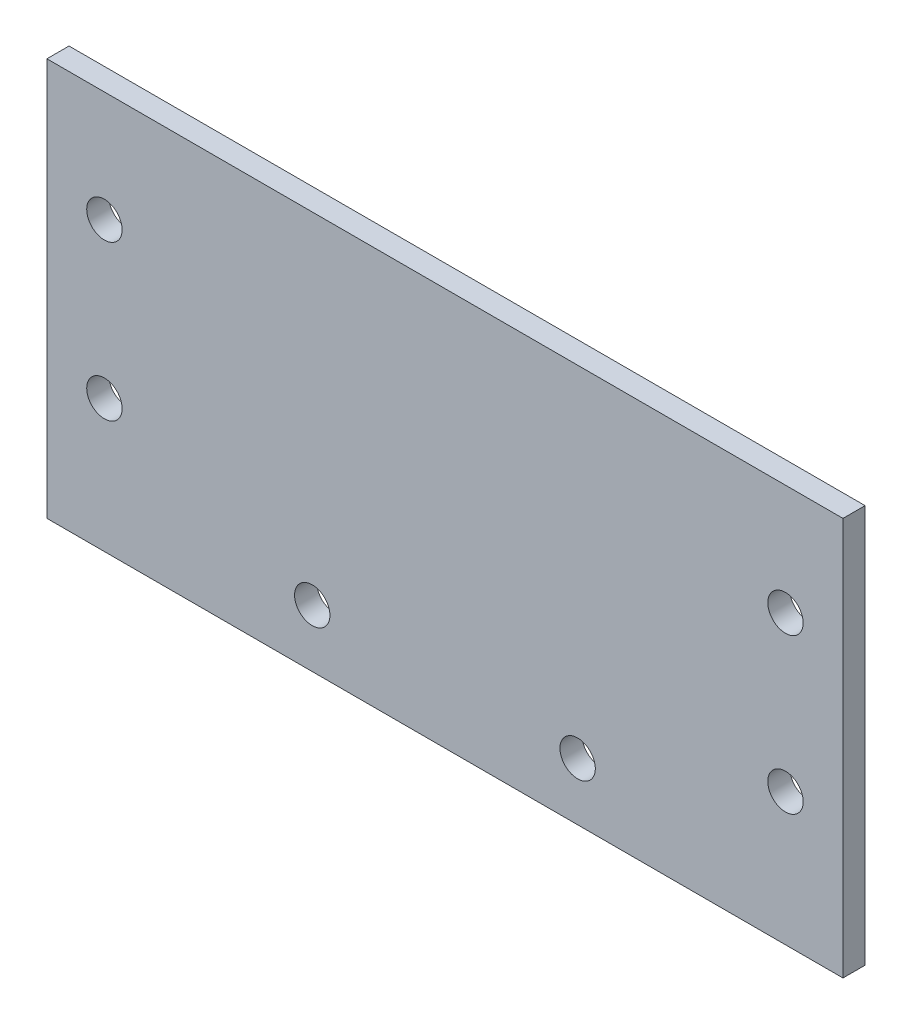
SolidWorks part; units mm, degrees
ref_plane "Front Plane" through (0, 0, 0) normal (0, 0, 1) x (1, 0, 0)
ref_plane "Top Plane" through (0, 0, 0) normal (0, 1, 0) x (1, 0, 0)
ref_plane "Right Plane" through (0, 0, 0) normal (1, 0, 0) x (0, 0, -1)
sketch "Sketch1" plane through (0, 0, 0) normal (0, 0, 1) x (1, 0, 0)
  line L1 (0, 0) -> (180, 0)
  line L2 (0, 0) -> (0, 90)
  line L3 (0, 90) -> (180, 90)
  line L4 (180, 0) -> (180, 90)
  dimension "D1" = 90
  dimension "D2" = 180
extrude "Boss-Extrude1" add sketch "Sketch1" along normal blind 5
hole_wizard "Ø1.0mm Dowel Hole1" positions "Sketch3" profile "Sketch4" hole size "Ø1.0" standard "ISO" end condition through all
sketch "Sketch3" plane through (0, 0, 0) normal (0, 0, -1) x (-1, 0, 0)
  line L0 (-180, 0) -> (-180, 90) construction
  line L1 (0, 0) -> (-180, 0) construction
  line L3 (-13, 65) -> (-13, 30) construction
  line L5 (0, 90) -> (0, 0) construction
  line L6 (-120, 13) -> (-60, 13) construction
  point P0 (-167, 65)
  point P2 (-167, 30)
  point P4 (-120, 13)
  point P6 (-60, 13)
  point P8 (-13, 30)
  point P10 (-13, 65)
  dimension "D1" = 13
  dimension "D2" = 13
  dimension "D3" = 30
  dimension "D4" = 35
  dimension "D5" = 13
  dimension "D6" = 30
  dimension "D7" = 35
  dimension "D8" = 47
  dimension "D9" = 107
  dimension "D10" = 13
sketch "Sketch4" plane through (167, 65, 0) normal (1, 0, 0) x (0, 1, 0)
  line L0 (0, 0) -> (0, 5)
  line L1 (0, 5) -> (4, 5)
  line L2 (4, 5) -> (4, 0)
  line L5 (4, 0) -> (0, 0)
  line L11 (0, -6.35) -> (0, 107.95) construction
  dimension "Thru Hole Dia." = 8
  dimension "Thru Hole Depth" = 5
